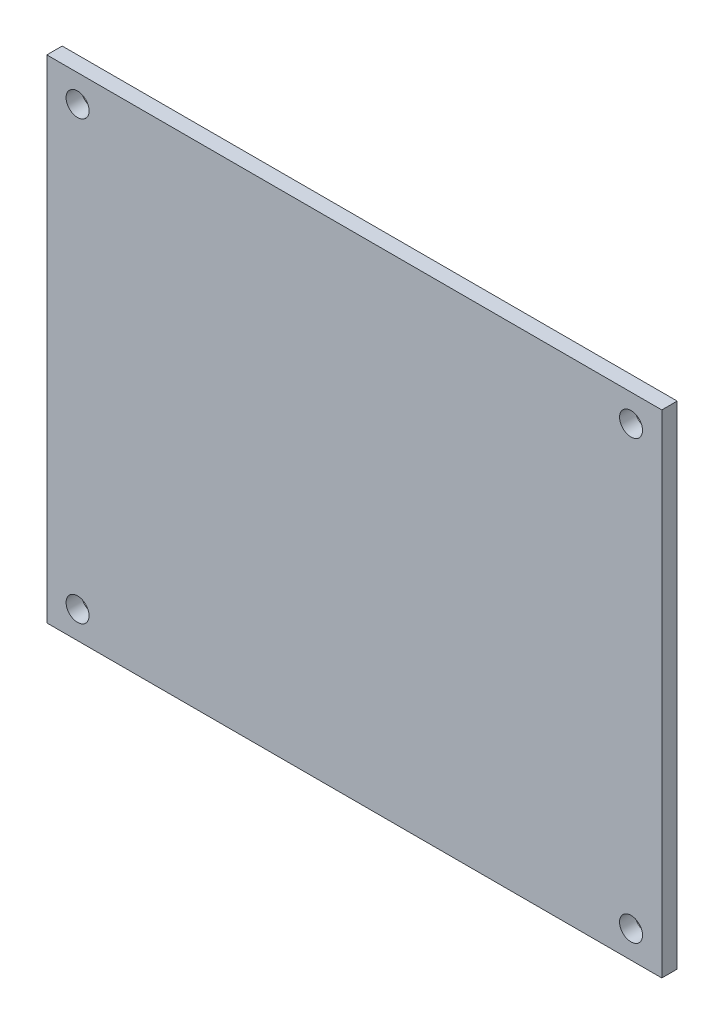
SolidWorks part; units mm, degrees
ref_plane "Front Plane" through (0, 0, 0) normal (0, 0, 1) x (1, 0, 0)
ref_plane "Top Plane" through (0, 0, 0) normal (0, 1, 0) x (1, 0, 0)
ref_plane "Right Plane" through (0, 0, 0) normal (1, 0, 0) x (0, 0, -1)
sketch "Sketch1" plane through (0, 0, 0) normal (0, 0, 1) x (1, 0, 0)
  line L1 (-127, 101.6) -> (127, 101.6)
  line L2 (-127, 101.6) -> (-127, -101.6)
  line L3 (-127, -101.6) -> (127, -101.6)
  line L4 (127, 101.6) -> (127, -101.6)
  line L5 (-127, 101.6) -> (127, -101.6) construction
  line L6 (-127, -101.6) -> (127, 101.6) construction
  point P0 (0, 0)
  dimension "D1" = 254
  dimension "D2" = 203.2
extrude "Boss-Extrude1" add sketch "Sketch1" along normal blind 6.35
sketch "Sketch2" plane through (0, 0, 6.35) normal (0, 0, 1) x (1, 0, 0)
  line L0 (114.3, -101.6) -> (114.3, -90.297) construction
  line L1 (127, -101.6) -> (101.6, -101.6) construction
  line L2 (127, -101.6) -> (127, -76.2) construction
  line L3 (127, -76.2) -> (101.6, -76.2) construction
  line L4 (101.6, -101.6) -> (101.6, -76.2) construction
  line L5 (0, -304.8) -> (0, 101.6) construction
  line L7 (127, 101.6) -> (-127, 101.6) construction
  line L8 (-381, 0) -> (127, 0) construction
  line L10 (127, -101.6) -> (127, 101.6) construction
  circle A0 centre (114.3, -90.297) radius 4.7498
  circle A1 centre (-114.3, -90.297) radius 4.7498
  circle A2 centre (114.3, 90.297) radius 4.7498
  circle A3 centre (-114.3, 90.297) radius 4.7498
  point P11 (0, -101.6)
  point P16 (-127, 0)
  dimension "D4" = 9.4996
  dimension "D1" = 25.4
  dimension "D2" = 25.4
  dimension "D3" = 11.303
extrude "Cut-Extrude2" cut sketch "Sketch2" against normal blind 6.35
sketch "Sketch3" plane through (0, 0, 6.35) normal (0, 0, 1) x (1, 0, 0)
  line L0 (0, -304.8) -> (0, 101.6) construction
  line L2 (127, 101.6) -> (-127, 101.6) construction
  line L3 (-381, 0) -> (127, 0) construction
  line L5 (127, -101.6) -> (127, 101.6) construction
  point P3 (0, -101.6)
  point P8 (-127, 0)
